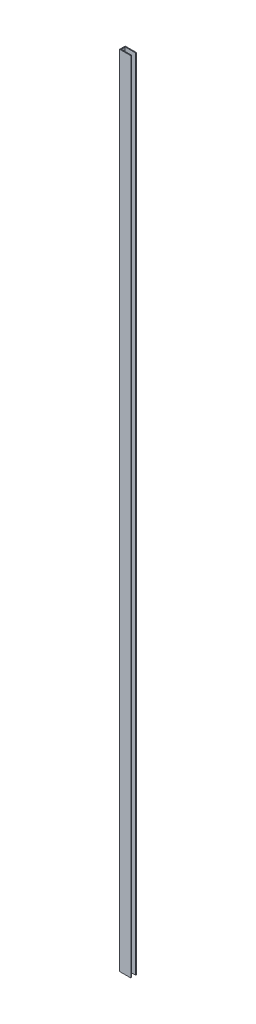
SolidWorks part; units mm, degrees
ref_plane "Спереди" through (0, 0, 0) normal (0, 0, 1) x (1, 0, 0)
ref_plane "Сверху" through (0, 0, 0) normal (0, 1, 0) x (1, 0, 0)
ref_plane "Справа" through (0, 0, 0) normal (1, 0, 0) x (0, 0, -1)
sketch "Эскиз2" plane through (0, 0, 0) normal (0, 1, 0) x (1, 0, 0)
  line L0 (0, -7) -> (0, 7)
  line L1 (0, 7) -> (28, 7)
  line L2 (28, 7) -> (28, 5)
  line L3 (28, 5) -> (2, 5)
  line L4 (2, 5) -> (2, -5)
  line L5 (2, -5) -> (28, -5)
  line L6 (28, -5) -> (28, -7)
  line L7 (28, -7) -> (0, -7)
  line L8 (2, 0) -> (0, 0) construction
  point P4 (0, 0)
  dimension "D1" = 2
  dimension "D2" = 28
  dimension "D3" = 10
extrude "Бобышка-Вытянуть1" add sketch "Эскиз2" along normal blind 2000 contours L1 L2 L3 L4 L5 L6 L7 L0
